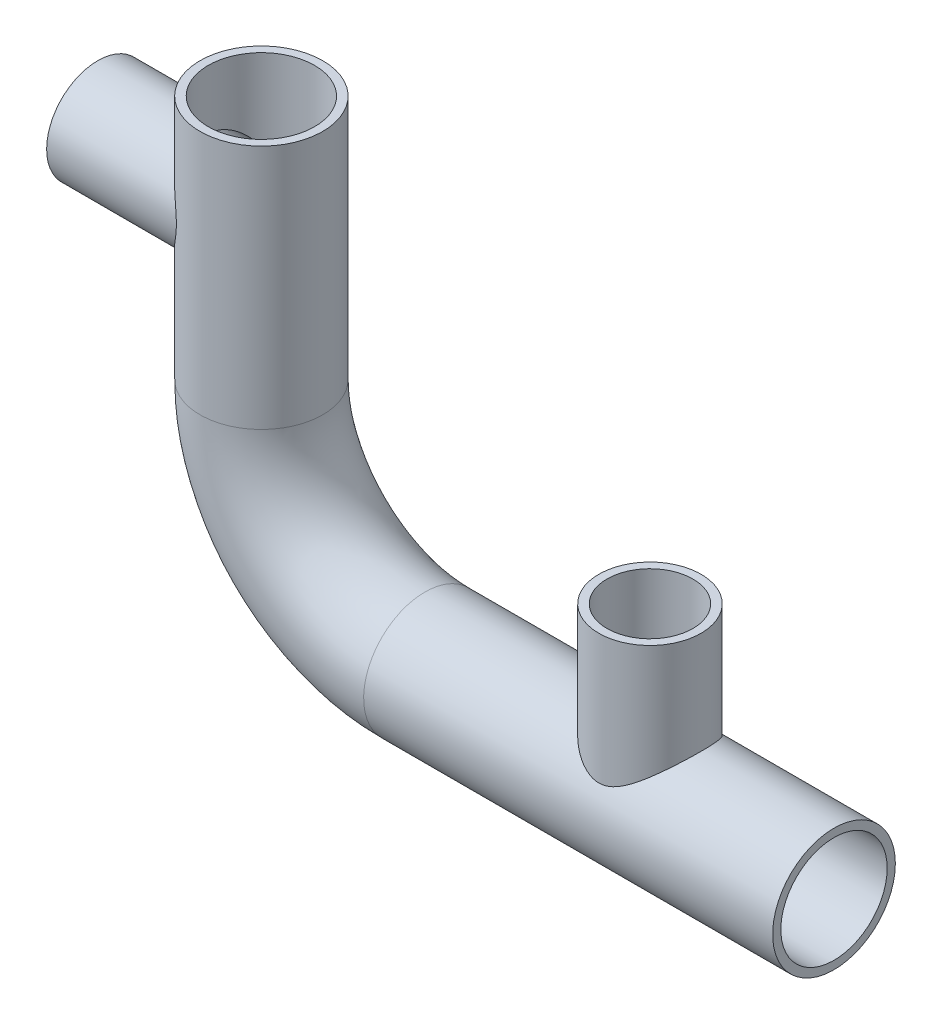
SolidWorks part; units mm, degrees
ref_plane "정면" through (0, 0, 0) normal (0, 0, 1) x (1, 0, 0)
ref_plane "윗면" through (0, 0, 0) normal (0, 1, 0) x (1, 0, 0)
ref_plane "우측면" through (0, 0, 0) normal (1, 0, 0) x (0, 0, -1)
sketch "스케치1" plane through (0, 0, 0) normal (0, 0, 1) x (1, 0, 0)
  line L0 (0, 100) -> (0, 40)
  line L1 (40, 0) -> (140, 0)
  arc A0 (40, 0) -> (0, 40) centre (40, 40) cw
  point P6 (0, 0)
  dimension "D3" = 40
  dimension "D1" = 100
  dimension "D2" = 140
ref_plane "평면1" through (140, 0, 0) normal (1, 0, 0) x (0, 0, -1)
sketch "스케치2" plane through (140, 0, 0) normal (1, 0, 0) x (0, 0, -1)
  circle A0 centre (0, 0) radius 15
  dimension "D1" = 30
sweep "스윕1" add profiles "스케치2" path "스케치1"
ref_plane "평면2" through (0, 40, 0) normal (0, 1, 0) x (1, 0, 0)
sketch "스케치3" plane through (0, 40, 0) normal (0, 1, 0) x (1, 0, 0)
  line L0 (140, -16.5) -> (140, 16.5) construction
  circle A0 centre (95, 0) radius 12.5
  dimension "D1" = 25
  dimension "D2" = 45
extrude "보스-돌출1" add sketch "스케치3" against normal up to next contours A0
ref_plane "평면3" through (-40, 0, 0) normal (1, 0, 0) x (0, 0, -1)
sketch "스케치4" plane through (-40, 0, 0) normal (1, 0, 0) x (0, 0, -1)
  circle A0 centre (0, 75) radius 12.5
  dimension "D2" = 25
  dimension "D1" = 25
extrude "보스-돌출2" add sketch "스케치4" along normal up to next
shell "쉘1" thickness 2
